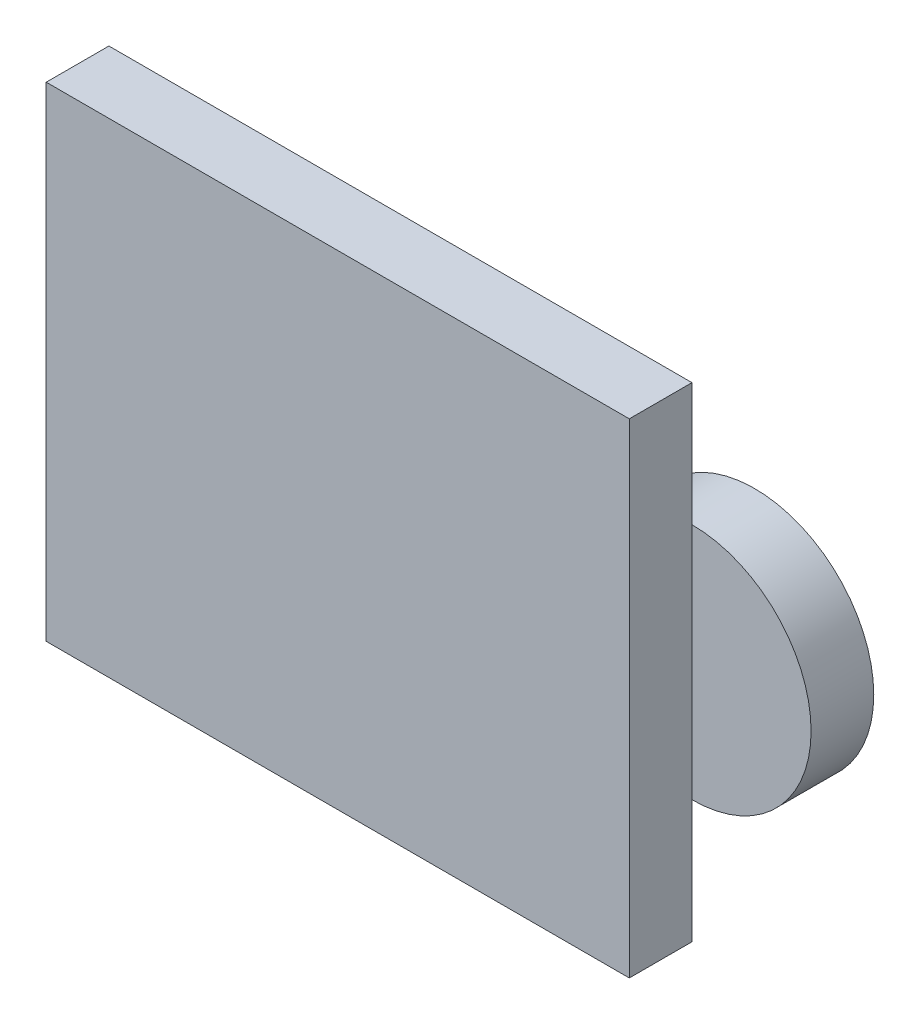
SolidWorks part; units mm, degrees
ref_plane "Спереди" through (0, 0, 0) normal (0, 0, 1) x (1, 0, 0)
ref_plane "Сверху" through (0, 0, 0) normal (0, 1, 0) x (1, 0, 0)
ref_plane "Справа" through (0, 0, 0) normal (1, 0, 0) x (0, 0, -1)
sketch "Эскиз1_fr" plane through (0, 0, 0) normal (0, 0, 1) x (1, 0, 0)
  line L1 (-48.994, 38.0205) -> (44.0482, 38.0205)
  line L2 (-48.994, 38.0205) -> (-48.994, -39.257)
  line L3 (-48.994, -39.257) -> (44.0482, -39.257)
  line L4 (44.0482, 38.0205) -> (44.0482, -39.257)
extrude "Бобышка-Вытянуть1" add sketch "Эскиз1_fr" along normal blind 10
sketch "Эскиз2" plane through (0, 0, 0) normal (0, 0, 1) x (1, 0, 0)
  line L0 (44.0482, -39.257) -> (44.0482, 38.0205) construction
  circle A0 centre (44.0482, -0.6182) radius 19.0086
extrude "Бобышка-Вытянуть2" add sketch "Эскиз2" against normal blind 10
